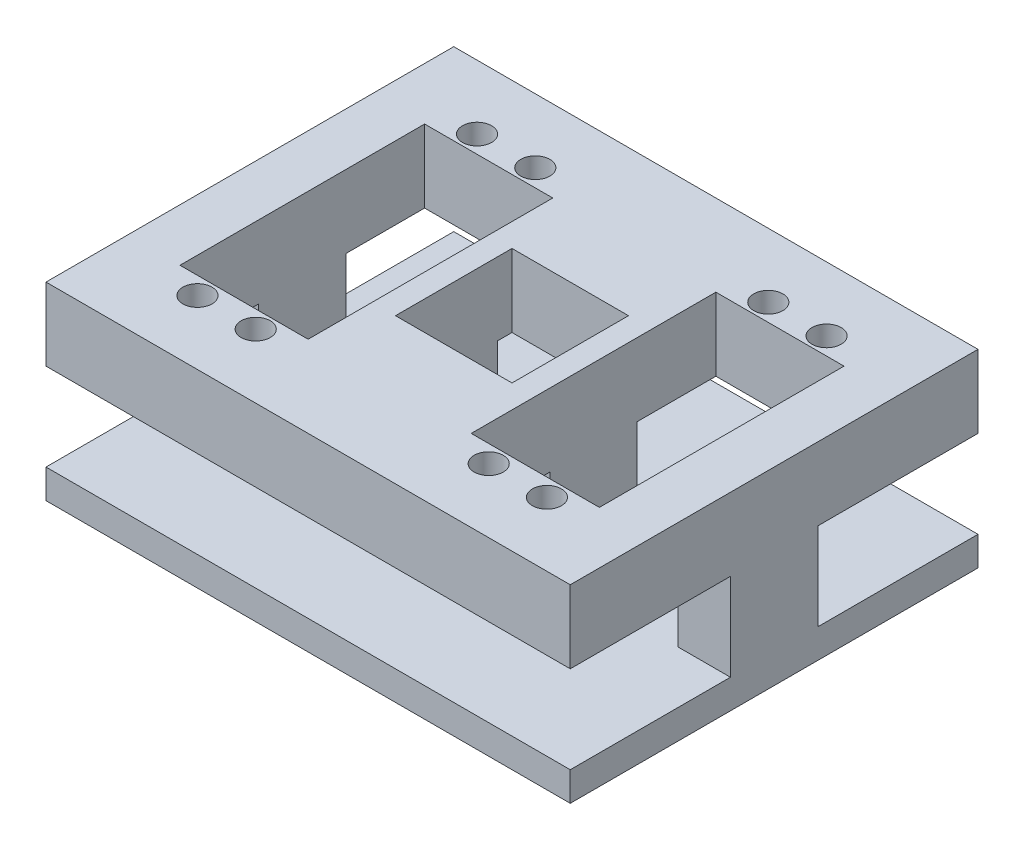
SolidWorks part; units mm, degrees
ref_plane "Front Plane" through (0, 0, 0) normal (0, 0, 1) x (1, 0, 0)
ref_plane "Top Plane" through (0, 0, 0) normal (0, 1, 0) x (1, 0, 0)
ref_plane "Right Plane" through (0, 0, 0) normal (1, 0, 0) x (0, 0, -1)
sketch "Sketch1" plane through (0, 0, 0) normal (0, 1, 0) x (1, 0, 0)
  line L0 (0, 74.7873) -> (0, -69.1899) construction
  line L1 (-45, 35) -> (45, 35)
  line L2 (-45, 35) -> (-45, -35)
  line L3 (-45, -35) -> (45, -35)
  line L4 (45, 35) -> (45, -35)
  line L5 (-45, 35) -> (45, -35) construction
  line L6 (-45, -35) -> (45, 35) construction
  line L7 (-36, 21) -> (-14, 21)
  line L8 (-36, 21) -> (-36, -21)
  line L9 (-36, -21) -> (-14, -21)
  line L10 (-14, 21) -> (-14, -21)
  line L11 (-36, 21) -> (-14, -21) construction
  line L12 (-36, -21) -> (-14, 21) construction
  line L13 (-120.0494, 0) -> (109.3545, 0) construction
  line L14 (45, 35) -> (-45, -35) construction
  line L15 (36, -21) -> (14, -21)
  line L16 (14, 21) -> (14, -21)
  line L17 (36, 21) -> (14, 21)
  line L18 (36, 21) -> (36, -21)
  line L24 (-10, 10) -> (10, -10) construction
  line L25 (-10, -10) -> (10, 10) construction
  circle A0 centre (-30, 24) radius 2.5
  circle A1 centre (-20, 24) radius 2.5
  circle A2 centre (-20, -24) radius 2.5
  circle A3 centre (-30, -24) radius 2.5
  circle A4 centre (20, -24) radius 2.5
  circle A5 centre (30, -24) radius 2.5
  circle A6 centre (20, 24) radius 2.5
  circle A7 centre (30, 24) radius 2.5
  point P0 (0, 0)
  point P6 (-25, 0)
  point P35 (0, 0)
  dimension "D6" = 5
  dimension "D7" = 5
  dimension "D1" = 90
  dimension "D2" = 70
  dimension "D3" = 22
  dimension "D4" = 42
  dimension "D5" = 0
  dimension "D8" = 10
  dimension "D9" = 24
  dimension "D10" = 24
  dimension "D11" = 6
  dimension "D12" = 25
  dimension "D13" = 20
  dimension "D14" = 20
  dimension "D15" = 28
extrude "Boss-Extrude1" add sketch "Sketch1" along normal blind 12.5
sketch "Sketch3" plane through (0, 0, 0) normal (0, -1, 0) x (1, 0, 0)
  line L0 (-45, -35) -> (-45, 35) construction
  line L1 (-45, 7.5) -> (45, 7.5)
  line L2 (-45, 7.5) -> (-45, -7.5)
  line L3 (-45, -7.5) -> (45, -7.5)
  line L4 (45, 7.5) -> (45, -7.5)
  line L5 (45, 35) -> (45, -35) construction
  line L6 (-45, 35) -> (45, 35) construction
  line L7 (-36, -21) -> (-36, 21) construction
  line L8 (-45, 7.5) -> (-36, 7.5)
  line L9 (-45, 7.5) -> (-45, -7.5)
  line L10 (-45, -7.5) -> (-36, -7.5)
  line L11 (-36, 7.5) -> (-36, -7.5)
  line L12 (-14, 21) -> (-14, -21) construction
  line L13 (-14, 7.5) -> (14, 7.5)
  line L14 (-14, 7.5) -> (-14, -7.5)
  line L15 (-14, -7.5) -> (14, -7.5)
  line L16 (14, 7.5) -> (14, -7.5)
  line L17 (14, -21) -> (14, 21) construction
  line L18 (36, 21) -> (36, -21) construction
  line L19 (36, 7.5) -> (45, 7.5)
  line L20 (36, 7.5) -> (36, -7.5)
  line L21 (36, -7.5) -> (45, -7.5)
  line L22 (45, 7.5) -> (45, -7.5)
  dimension "D1" = 15
  dimension "D2" = 27.5
extrude "Boss-Extrude2" add sketch "Sketch3" along normal blind 15 contours L9 L8 L11 L10 | L14 L13 L16 L15 | L20 L19 L22 L21
sketch "Sketch4" plane through (0, 12.5, 0) normal (0, 1, 0) x (1, 0, 0)
  line L1 (-10, 10) -> (10, 10)
  line L2 (-10, 10) -> (-10, -10)
  line L3 (-10, -10) -> (10, -10)
  line L4 (10, 10) -> (10, -10)
  line L5 (-10, 10) -> (10, -10) construction
  line L6 (-10, -10) -> (10, 10) construction
  point P0 (0, 0)
  dimension "D1" = 20
  dimension "D2" = 20
extrude "Cut-Extrude1" cut sketch "Sketch4" against normal through all
sketch "Sketch7" plane through (0, -15, 0) normal (0, -1, 0) x (1, 0, 0)
  line L0 (-45, 35) -> (45, 35) construction
  line L1 (-45, 35) -> (45, 35)
  line L2 (-45, 35) -> (-45, -35)
  line L3 (-45, -35) -> (45, -35)
  line L4 (45, 35) -> (45, -35)
  line L5 (-45, 7.5) -> (-45, 35) construction
  line L7 (-10, 10) -> (10, 10)
  line L8 (-10, 10) -> (-10, -10)
  line L9 (-10, -10) -> (10, -10)
  line L10 (10, 10) -> (10, -10)
  line L11 (-10, 10) -> (10, -10) construction
  line L12 (-10, -10) -> (10, 10) construction
  point P9 (0, 0)
extrude "Boss-Extrude3" add sketch "Sketch7" along normal blind 5
sketch "Sketch8" plane through (0, -20, 0) normal (0, -1, 0) x (1, 0, 0)
  circle A0 centre (0, 0) radius 26.5144
  circle A1 centre (0, 0) radius 2.5
  dimension "D1" = 5
extrude "Boss-Extrude4" add sketch "Sketch8" along normal blind 5
